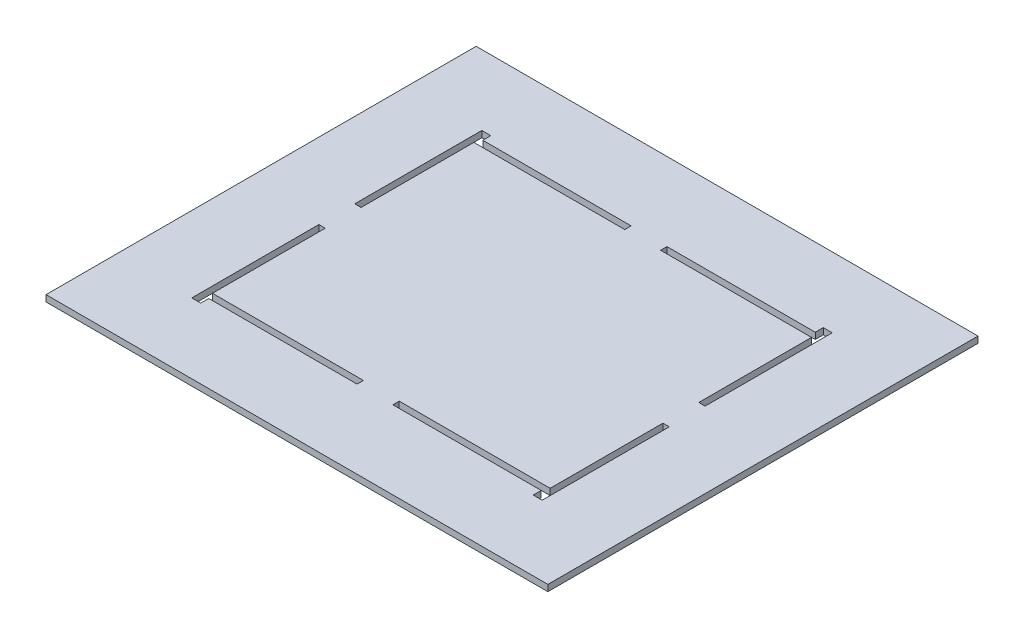
SolidWorks part; units mm, degrees
ref_plane "Front Plane" through (0, 0, 0) normal (0, 0, 1) x (1, 0, 0)
ref_plane "Top Plane" through (0, 0, 0) normal (0, 1, 0) x (1, 0, 0)
ref_plane "Right Plane" through (0, 0, 0) normal (1, 0, 0) x (0, 0, -1)
sketch "Sketch2" plane through (0, 0, 0) normal (0, 1, 0) x (1, 0, 0)
  line L1 (0, 0) -> (355.6, 0)
  line L2 (0, 0) -> (0, 304.8)
  line L3 (0, 304.8) -> (355.6, 304.8)
  line L4 (355.6, 0) -> (355.6, 304.8)
  dimension "D1" = 355.6
  dimension "D2" = 304.8
extrude "Boss-Extrude1" add sketch "Sketch2" along normal blind 4.4958
sketch "Sketch3" plane through (0, 4.4958, 0) normal (0, 1, 0) x (1, 0, 0)
  line L0 (355.6, 304.8) -> (0, 304.8) construction
  line L1 (60.0075, 55.3085) -> (295.5925, 55.3085)
  line L2 (53.6575, 53.4543) -> (53.6575, 251.3457)
  line L3 (60.0075, 249.4915) -> (295.5925, 249.4915)
  line L4 (301.9425, 53.4543) -> (301.9425, 251.3457)
  line L5 (0, 304.8) -> (0, 0) construction
  line L7 (58.1533, 59.8043) -> (297.4467, 59.8043)
  line L8 (58.1533, 59.8043) -> (58.1533, 244.9957)
  line L9 (58.1533, 244.9957) -> (297.4467, 244.9957)
  line L10 (297.4467, 59.8043) -> (297.4467, 244.9957)
  line L11 (165.1, 59.8043) -> (190.5, 59.8043)
  line L12 (165.1, 59.8043) -> (165.1, 55.3085)
  line L13 (165.1, 55.3085) -> (190.5, 55.3085)
  line L14 (190.5, 59.8043) -> (190.5, 55.3085)
  line L15 (53.6575, 165.1) -> (58.1533, 165.1)
  line L16 (53.6575, 165.1) -> (53.6575, 139.7)
  line L17 (53.6575, 139.7) -> (58.1533, 139.7)
  line L18 (58.1533, 165.1) -> (58.1533, 139.7)
  line L19 (165.1, 249.4915) -> (190.5, 249.4915)
  line L20 (165.1, 249.4915) -> (165.1, 244.9957)
  line L21 (165.1, 244.9957) -> (190.5, 244.9957)
  line L22 (190.5, 249.4915) -> (190.5, 244.9957)
  line L23 (301.9425, 165.1) -> (297.4467, 165.1)
  line L24 (301.9425, 165.1) -> (301.9425, 139.7)
  line L25 (301.9425, 139.7) -> (297.4467, 139.7)
  line L26 (297.4467, 165.1) -> (297.4467, 139.7)
  line L28 (53.6575, 251.3457) -> (53.6575, 255.1557)
  line L29 (53.6575, 255.1557) -> (60.0075, 255.1557)
  line L30 (60.0075, 249.4915) -> (60.0075, 255.1557)
  line L32 (301.9425, 251.3457) -> (301.9425, 255.1557)
  line L33 (301.9425, 255.1557) -> (295.5925, 255.1557)
  line L34 (295.5925, 249.4915) -> (295.5925, 255.1557)
  line L36 (301.9425, 53.4543) -> (301.9425, 49.6443)
  line L37 (301.9425, 49.6443) -> (295.5925, 49.6443)
  line L38 (295.5925, 55.3085) -> (295.5925, 49.6443)
  line L40 (53.6575, 53.4543) -> (53.6575, 49.6443)
  line L41 (53.6575, 49.6443) -> (60.0075, 49.6443)
  line L42 (60.0075, 55.3085) -> (60.0075, 49.6443)
  point P6 (177.8, 304.8)
  point P7 (177.8, 249.4915)
  point P10 (0, 152.4)
  point P11 (53.6575, 152.4)
  point P32 (177.8, 59.8043)
  point P33 (177.8, 59.8043)
  point P34 (58.1533, 152.4)
  point P35 (58.1533, 152.4)
  dimension "D1" = 248.285
  dimension "D2" = 197.8914
  dimension "D3" = 4.4958
  dimension ".177" = 4.4958
  dimension "D5" = 4.4958
  dimension "D6" = 4.4958
  dimension "D7" = 25.4
  dimension "D8" = 25.4
  dimension "D9" = 25.4
  dimension "D10" = 25.4
  dimension "D11" = 3.81
extrude "Cut-Extrude3" cut sketch "Sketch3" against normal blind 6.35 contours L20 L3 L2 L15 L8 L9 | L17 L2 L1 L12 L7 L8 | L4 L25 L10 L7 L14 L1 | L23 L4 L3 L22 L9 L10
